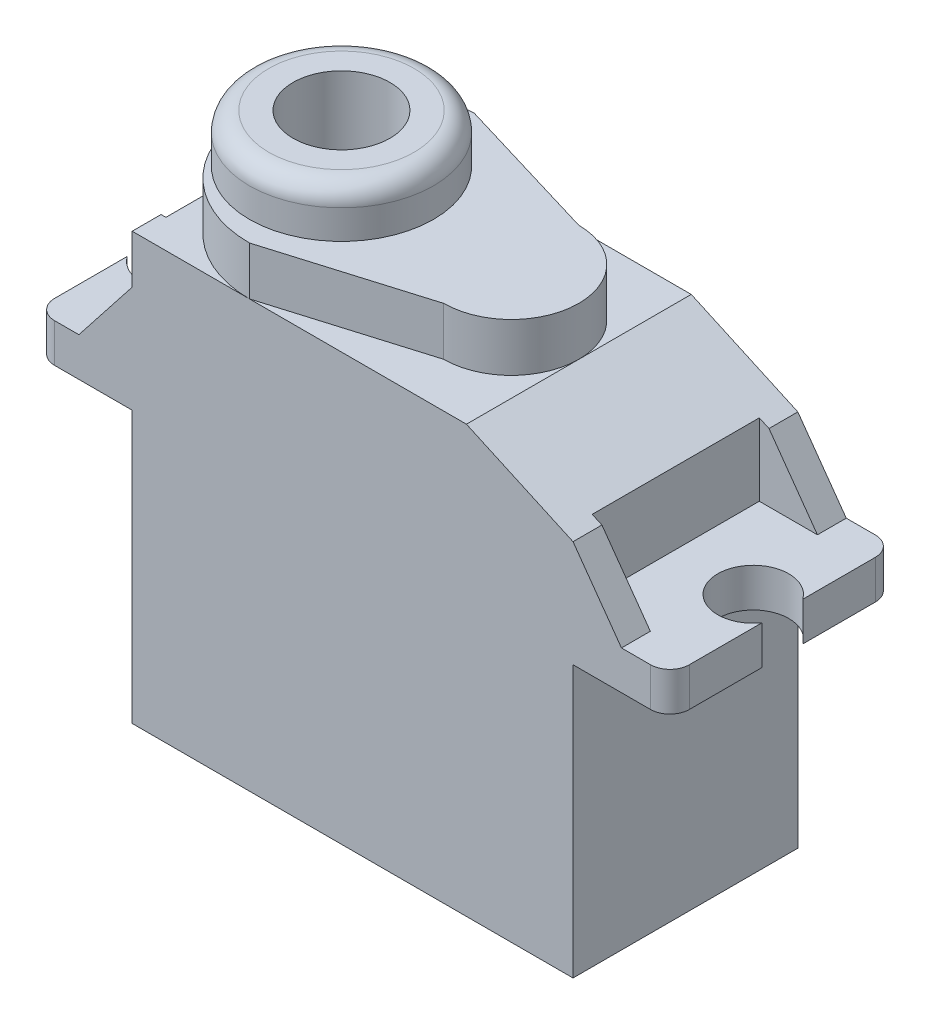
SolidWorks part; units mm, degrees
material "BUTYL"
ref_plane "Front Plane" through (0, 0, 0) normal (0, 0, 1) x (1, 0, 0)
ref_plane "Top Plane" through (0, 0, 0) normal (0, 1, 0) x (1, 0, 0)
ref_plane "Right Plane" through (0, 0, 0) normal (1, 0, 0) x (0, 0, -1)
sketch "Sketch1" plane through (0, 0, 0) normal (0, 0, 1) x (1, 0, 0)
  line L0 (-9.9924, 0) -> (12.7576, 0)
  line L1 (12.7576, 0) -> (12.7576, 14)
  line L2 (12.7576, 14) -> (17.7576, 14)
  line L3 (17.7576, 14) -> (17.7576, 16)
  line L4 (17.7576, 16) -> (-14.9924, 16)
  line L5 (-14.9924, 16) -> (-14.9924, 14)
  line L6 (-14.9924, 14) -> (-9.9924, 14)
  line L7 (-9.9924, 14) -> (-9.9924, 0)
  point P9 (-14.9924, 15)
  dimension "D1" = 32.75
  dimension "D2" = 22.75
  dimension "D3" = 5
  dimension "D4" = 2
  dimension "D5" = 16
extrude "Boss-Extrude1" add sketch "Sketch1" along normal blind 11.6
sketch "Sketch2" plane through (0, 16, 0) normal (0, 1, 0) x (1, 0, 0)
  line L0 (-14.9924, -5.8) -> (17.7576, -5.8) construction
  line L1 (-14.9924, -11.6) -> (-14.9924, 0) construction
  line L2 (17.7576, -11.6) -> (17.7576, 0) construction
  circle A0 centre (-13.4924, -5.8) radius 1.8339
  circle A1 centre (16.2576, -5.8) radius 1.8339
  dimension "D1" = 3.6678
  dimension "D2" = 1.5
  dimension "D3" = 1.5
extrude "Cut-Extrude1" cut sketch "Sketch2" against normal blind 11.6
sketch "Sketch3" plane through (0, 16, 0) normal (0, 1, 0) x (1, 0, 0)
  line L0 (17.7576, 0) -> (-14.9924, 0) construction
  line L1 (-12.7424, 0) -> (15.2576, 0)
  line L2 (-12.7424, 0) -> (-12.7424, -11.6)
  line L3 (-12.7424, -11.6) -> (15.2576, -11.6)
  line L4 (15.2576, 0) -> (15.2576, -11.6)
  line L5 (17.7576, -11.6) -> (-14.9924, -11.6) construction
  line L7 (-14.9924, -4.745) -> (-14.9924, 0) construction
  dimension "D1" = 28
  dimension "D2" = 2.25
extrude "Boss-Extrude2" add sketch "Sketch3" along normal blind 6
sketch "Sketch4" plane through (0, 22, 0) normal (0, 1, 0) x (1, 0, 0)
  line L0 (-12.7424, 0) -> (-12.7424, -11.6) construction
  line L1 (-12.7424, -1.4873) -> (-9.7424, -1.4873)
  line L2 (-12.7424, -1.4873) -> (-12.7424, -10.11)
  line L3 (-12.7424, -10.11) -> (-9.7424, -10.11)
  line L4 (-9.7424, -1.4873) -> (-9.7424, -10.11)
  line L5 (15.2576, -4.2628) -> (15.2576, 0) construction
  line L6 (15.2576, -1.4873) -> (12.2576, -1.4873)
  line L7 (15.2576, -1.4873) -> (15.2576, -10.11)
  line L8 (15.2576, -10.11) -> (12.2576, -10.11)
  line L9 (12.2576, -1.4873) -> (12.2576, -10.11)
  line L10 (15.2576, 0) -> (-12.7424, 0) construction
  line L11 (-12.7424, -11.6) -> (15.2576, -11.6) construction
  point P12 (-9.7424, -5.7986)
  dimension "D1" = 3
  dimension "D2" = 3
  dimension "D3" = 1.4873
  dimension "D4" = 1.49
extrude "Cut-Extrude2" cut sketch "Sketch4" against normal blind 6
sketch "Sketch5" plane through (0, 0, 11.6) normal (0, 0, 1) x (1, 0, 0)
  line L0 (-9.9924, 22) -> (-9.9924, 19.5)
  line L1 (-12.7424, 22) -> (15.2576, 22) construction
  line L2 (-9.9924, 19.5) -> (-12.7424, 16)
  line L3 (-12.7424, 16) -> (-12.7424, 22)
  line L4 (-12.7424, 22) -> (-9.9924, 22)
  line L5 (15.2576, 16) -> (12.7576, 19.5)
  line L6 (12.7576, 19.5) -> (7.2576, 22)
  line L7 (7.2576, 22) -> (15.2576, 22)
  line L8 (15.2576, 22) -> (15.2576, 16)
  dimension "D1" = 3.5
  dimension "D2" = 8
extrude "Cut-Extrude3" cut sketch "Sketch5" against normal blind 12
sketch "Sketch6" plane through (0, 22, 0) normal (0, 1, 0) x (1, 0, 0)
  line L0 (-9.7424, -5.7986) -> (7.2576, -5.8) construction
  line L1 (-9.7424, -10.11) -> (-9.7424, -1.4873) construction
  line L2 (7.2576, 0) -> (7.2576, -11.6) construction
  line L3 (-9.7424, -10.11) -> (-9.7424, -1.4873) construction
  line L4 (-9.9924, -11.6) -> (7.2576, -11.6) construction
  line L5 (-3.9415, 0.0018) -> (3.7707, -2.3128)
  line L6 (-3.9415, -11.6) -> (3.7707, -9.2866)
  arc A0 (-3.9415, 0.0018) -> (-3.9415, -11.6) centre (-3.9415, -5.7991) ccw
  arc A1 (3.7707, -9.2866) -> (3.7707, -2.3128) centre (3.7707, -5.7997) ccw
  dimension "D1" = 3.4869
extrude "Boss-Extrude3" add sketch "Sketch6" along normal blind 2.5
sketch "Sketch7" plane through (0, 24.5, 0) normal (0, 1, 0) x (1, 0, 0)
  line L0 (-9.7424, -5.7986) -> (7.2576, -5.7997) construction
  line L1 (-9.7424, -10.11) -> (-9.7424, -1.4873) construction
  line L2 (-14.9924, -4.745) -> (-14.9924, 0) construction
  arc A0 (3.7707, -9.2866) -> (3.7707, -2.3128) centre (3.7707, -5.7997) ccw construction
  circle A1 centre (-4.9924, -5.7989) radius 4.75
  dimension "D1" = 10
extrude "Boss-Extrude4" add sketch "Sketch7" along normal blind 2.5
sketch "Sketch8" plane through (0, 27, 0) normal (0, 1, 0) x (1, 0, 0)
  circle A0 centre (-4.9924, -5.7989) radius 2.5
  dimension "D1" = 5
extrude "Cut-Extrude4" cut sketch "Sketch8" against normal blind 5
fillet "Fillet1" radius 1 5 edges at (-4.9924, 27, 10.5489) (-14.9924, 15, 11.6) (-14.9924, 15, 0) (17.7576, 15, 0) (17.7576, 15, 11.6)
